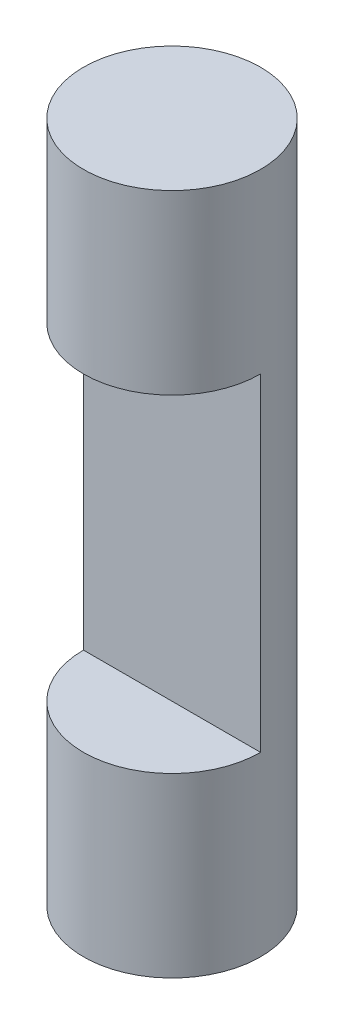
SolidWorks part; units mm, degrees
material "ABS"
ref_plane "Front Plane" through (0, 0, 0) normal (0, 0, 1) x (1, 0, 0)
ref_plane "Top Plane" through (0, 0, 0) normal (0, 1, 0) x (1, 0, 0)
ref_plane "Right Plane" through (0, 0, 0) normal (1, 0, 0) x (0, 0, -1)
sketch "Sketch1" plane through (0, 0, 0) normal (0, 1, 0) x (1, 0, 0)
  circle A0 centre (0, 0) radius 13
  dimension "D1" = 26
extrude "Boss-Extrude1" add sketch "Sketch1" along normal blind 1
ref_plane "Plane1" through (0, 1, 0) normal (0, 1, 0) x (1, 0, 0)
ref_plane "Plane2" through (0, 4.7, 0) normal (0, 1, 0) x (1, 0, 0)
ref_plane "Plane3" through (0, 9.7, 0) normal (0, 1, 0) x (1, 0, 0)
ref_plane "Plane4" through (0, 13.4, 0) normal (0, 1, 0) x (1, 0, 0)
ref_plane "Plane5" through (0, 18.4, 0) normal (0, 1, 0) x (1, 0, 0)
ref_plane "Plane6" through (0, 22.1, 0) normal (0, 1, 0) x (1, 0, 0)
ref_plane "Plane7" through (0, 27.1, 0) normal (0, 1, 0) x (1, 0, 0)
ref_plane "Plane8" through (0, 30.8, 0) normal (0, 1, 0) x (1, 0, 0)
sketch "Sketch16" plane through (0, 30.8, 0) normal (0, 1, 0) x (1, 0, 0)
  circle A0 centre (0, 0) radius 13
  circle A1 centre (0, 0) radius 13 construction
  dimension "D1" = 0
extrude "Boss-Extrude3" add sketch "Sketch16" along normal blind 1 separate body
sketch "Sketch18" plane through (0, 4.7, 0) normal (0, 1, 0) x (1, 0, 0)
  line L1 (-11, -11) -> (11, -11)
  line L2 (-11, -11) -> (-11, 11)
  line L3 (-11, 11) -> (11, 11)
  line L4 (11, -11) -> (11, 11)
  dimension "D1" = 22
  dimension "D2" = 22
  dimension "D3" = 11
  dimension "D4" = 11
sketch "Sketch19" plane through (0, 1, 0) normal (0, 1, 0) x (1, 0, 0)
  circle A0 centre (0, 11) radius 1
  point P13 (0, 0)
  dimension "D1" = 2
  dimension "D2" = 11
extrude "Boss-Extrude4" add sketch "Sketch19" along normal up to surface (29.8 mm away) up to face at (0, 30.8, 13)
extrude "Cut-Extrude6" cut sketch "Sketch18" against normal blind 3.7
sketch "Sketch21" plane through (0, 13.4, 0) normal (0, 1, 0) x (1, 0, 0)
  circle A0 centre (0, 0) radius 11
  dimension "D1" = 22
extrude "Cut-Extrude7" cut sketch "Sketch21" against normal blind 3.7
sketch "Sketch22" plane through (0, 22.1, 0) normal (0, 1, 0) x (1, 0, 0)
  circle A0 centre (0, 0) radius 11
  dimension "D1" = 22
extrude "Cut-Extrude8" cut sketch "Sketch22" against normal blind 3.7
sketch "Sketch23" plane through (0, 30.8, 0) normal (0, 1, 0) x (1, 0, 0)
  circle A0 centre (0, 0) radius 11
  dimension "D1" = 22
extrude "Cut-Extrude9" cut sketch "Sketch23" against normal blind 3.7
sketch "Sketch24" plane through (0, 31.8, 0) normal (0, 1, 0) x (1, 0, 0)
  circle A0 centre (0, 0) radius 19.9218
extrude "Cut-Extrude10" cut sketch "Sketch24" against normal blind 1
sketch "Sketch25" plane through (0, 1, 0) normal (0, 1, 0) x (1, 0, 0)
  circle A0 centre (0, 0) radius 36.1829
extrude "Cut-Extrude11" cut sketch "Sketch25" against normal blind 1
sketch "Sketch26" plane through (0, 30.8, 0) normal (0, 1, 0) x (1, 0, 0)
  circle A0 centre (0, 11) radius 1
  arc A1 (0.999, 10.9545) -> (-0.999, 10.9545) centre (0, 0) ccw construction
  arc A2 (0.999, 10.9545) -> (-0.999, 10.9545) centre (0, 11) ccw construction
  arc M1 (0.999, 10.9545) -> (-0.999, 10.9545) centre (0, 11) ccw
  arc M2 (-0.999, 10.9545) -> (0.999, 10.9545) centre (0, 0) cw
  dimension "D1" = 0
extrude "Boss-Extrude5" add sketch "Sketch26" along normal blind 2 contours M2 M1 | A0 M2
sketch "Sketch27" plane through (0, 1, 0) normal (0, -1, 0) x (1, 0, 0)
  circle A0 centre (0, -11) radius 1
extrude "Boss-Extrude6" add sketch "Sketch27" along normal blind 2
sketch "Sketch28" plane through (0, 32.8, 0) normal (0, 1, 0) x (1, 0, 0)
  circle A0 centre (-0.3752, 0) radius 15.8574
extrude "Cut-Extrude12" cut sketch "Sketch28" against normal offset from surface (26.1 mm away) 2 up to face at (0, 4.7, -10.5)
